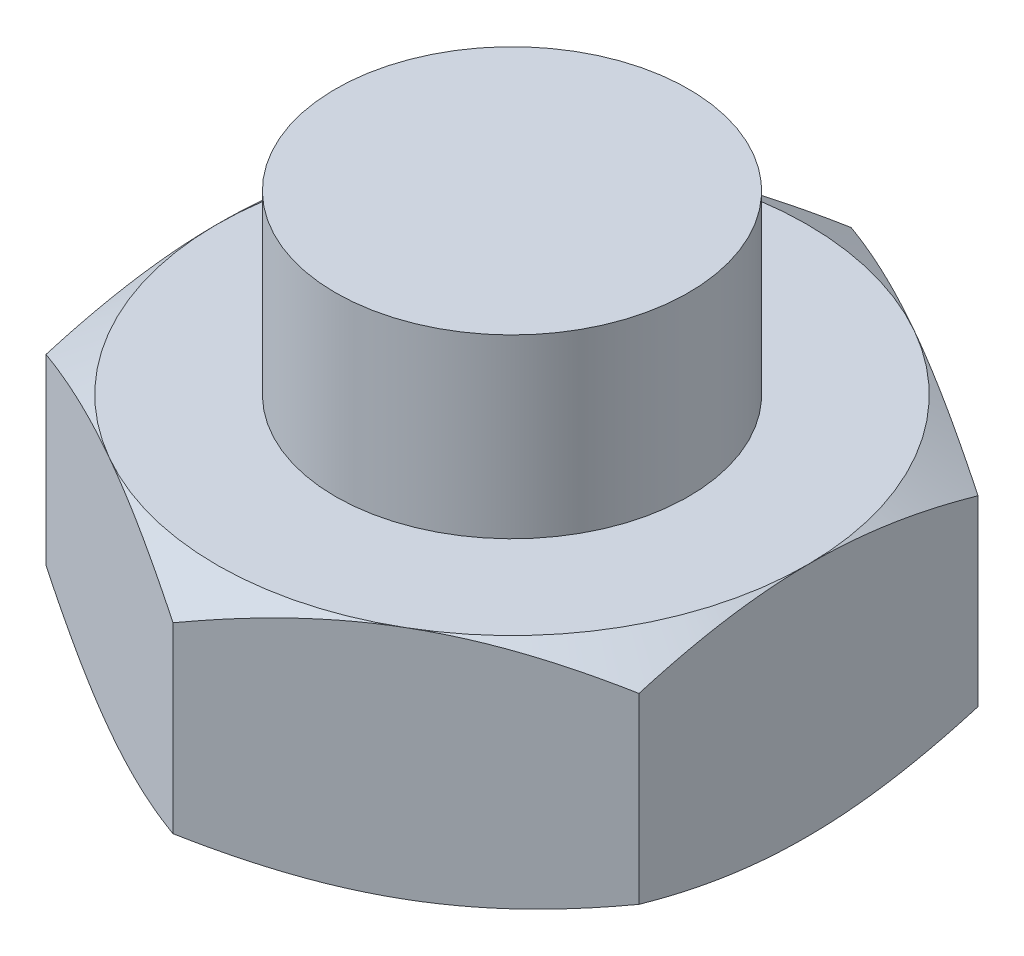
SolidWorks part; units mm, degrees
ref_plane "Front Plane" through (0, 0, 0) normal (0, 0, 1) x (1, 0, 0)
ref_plane "Top Plane" through (0, 0, 0) normal (0, 1, 0) x (1, 0, 0)
ref_plane "Right Plane" through (0, 0, 0) normal (1, 0, 0) x (0, 0, -1)
sketch "Sketch1" plane through (0, 0, 0) normal (0, 1, 0) x (1, 0, 0)
  line L1 (5, 2.9196) -> (-0.0285, 5.79)
  line L2 (-0.0285, 5.79) -> (-5.0285, 2.8703)
  line L3 (-5.0285, 2.8703) -> (-5, -2.9196)
  line L4 (-5, -2.9196) -> (0.0285, -5.79)
  line L5 (0.0285, -5.79) -> (5.0285, -2.8703)
  line L6 (5.0285, -2.8703) -> (5, 2.9196)
extrude "Boss-Extrude1" add sketch "Sketch1" along normal blind 4
sketch "Sketch2" plane through (0, 4, 0) normal (0, 1, 0) x (1, 0, 0)
  circle A0 centre (0, 0) radius 5.0143
extrude "Cut-Extrude1" cut sketch "Sketch2" against normal blind 4 draft 60 flip side to cut
sketch "Sketch3" plane through (0, 0, 0) normal (0, -1, 0) x (1, 0, 0)
  circle A0 centre (0, 0) radius 5.0143
extrude "Cut-Extrude2" cut sketch "Sketch3" against normal blind 4 draft 60 flip side to cut
sketch "Sketch4" plane through (0, 4, 0) normal (0, 1, 0) x (1, 0, 0)
  circle A0 centre (0, 0) radius 3
extrude "Boss-Extrude3" add sketch "Sketch4" along normal blind 3
